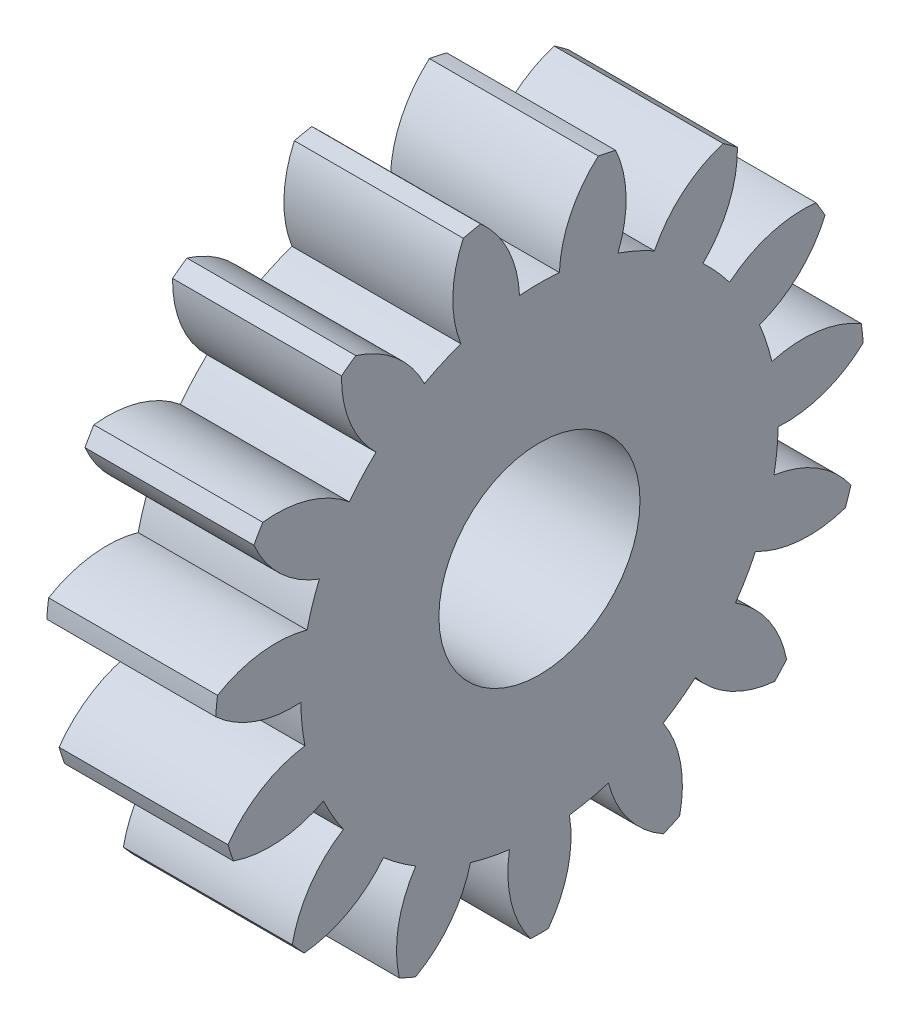
SolidWorks part; units mm, degrees
ref_plane "Plane1" through (0, 0, 0) normal (0, 0, 1) x (1, 0, 0)
ref_plane "Plane2" through (0, 0, 0) normal (0, 1, 0) x (1, 0, 0)
ref_plane "Plane3" through (0, 0, 0) normal (1, 0, 0) x (0, 0, -1)
sketch "HoldingSke" plane through (0, 0, 0) normal (0, 1, 0) x (1, 0, 0)
  line L0 (0, 0) -> (0.5084, -0.1362)
  line L1 (-15, 0) -> (100, 0) construction
  line L2 (0, 0) -> (-2.1039, 2.3779)
  line L3 (0, 0) -> (-11.863, 4.5341)
  line L4 (0, 0) -> (8.3417, 2.2352)
  line L5 (0, 0) -> (-46.8476, -17.4728)
  line L6 (0, 0) -> (-6.9633, -4.6982)
  line L7 (-2.1039, 2.3779) -> (8.6586, 51.2059)
  line L8 (-76.2, 54.61) -> (-74.4, 54.61)
  line L9 (-71.009, 38.7566) -> (-53.1078, 45.2721)
  line L10 (-76.2, 71.12) -> (104.1128, 71.12)
  line L11 (0, 0) -> (-8.4, 0)
  line L12 (-76.2, 101.6) -> (-76.14, 101.6)
  line L13 (24.9733, 27.94) -> (52.9518, 28.4284)
  line L14 (24.9733, 27.94) -> (24.9743, 27.94)
  line L15 (24.9733, 27.94) -> (100.4006, 29.5858)
  line L16 (-63.627, -1.9) -> (-12.827, -1.9)
  circle A0 centre (0, 0) radius 5
  circle A1 centre (0, 0) radius 11.874
  circle A2 centre (0, 0) radius 37.5
  circle A3 centre (0, 0) radius 5
  dimension "MHD" = 23.748
  dimension "Hub_dia" = 75
  dimension "Bore" = 10
  dimension "MBD" = 10
  dimension "Num_teeth" = 15
  dimension "Pitch" = 0.5263
  dimension "Overall_len" = 50
  dimension "Show_teeth" = 15
  dimension "Thickness" = 8.4
  dimension "OAL" = 50.0001
  dimension "T_dim" = 1.8
  dimension "Ap" = 20
  dimension "H" = 19.05
  dimension "Pitch_radius" = 180.3128
  dimension "Width" = 8.4
  dimension "Backlash" = 0.06
  dimension "Addendum_fac" = 1
  dimension "Dedendum_fac" = 1.25
  dimension "Clearance_fac" = 0.25
  dimension "Dedendum_add" = 0.001
  dimension "Module" = 1.9
sketch "BasProSke" plane through (0, 0, 0) normal (0, 1, 0) x (1, 0, 0)
  line L0 (-10, 0) -> (60, 0) construction
  line L1 (0, 0) -> (0, 16.15)
  line L2 (0, 0) -> (8.4, 0)
  line L3 (8.4, 0) -> (8.4, 16.15)
  line L4 (8.4, 16.15) -> (0, 16.15)
  dimension "Thickness" = 8.4
  dimension "Diameter" = 32.3
revolve "Base-Revolve" add sketch "BasProSke" angle 360 about L0
sketch "TooCutSke" plane through (0, 0, 0) normal (1, 0, 0) x (0, 0, -1)
  line L1 (0, 0) -> (0, 107) construction
  line L2 (0, 0) -> (-1.5944, 14.1605) construction
  line L3 (0, 0) -> (-5.8974, 27.7453) construction
  line L4 (-1.5944, 14.1605) -> (-2.9487, 13.8727) construction
  arc A0 (0.9922, 11.8325) -> (-0.9922, 11.8325) centre (0, 0) ccw
  arc A1 (2.9495, 15.9042) -> (-2.9495, 15.9042) centre (0, 0) ccw
  circle A2 centre (0, 0) radius 14.25 construction
  circle A3 centre (0, 0) radius 13.3906 construction
  arc A4 (-0.9922, 11.8325) -> (-2.9495, 15.9042) centre (-6.6875, 11.6011) ccw
  arc A5 (2.9495, 15.9042) -> (0.9922, 11.8325) centre (6.6875, 11.6011) ccw
  dimension "Root_dia" = 23.748
  dimension "Overcut_dia" = 32.3508
  dimension "Pitch_dia" = 28.5
  dimension "Base_dia" = 26.7812
  dimension "Flank_rad" = 5.7
  dimension "Half_ang" = 12
  dimension "Half_CT" = 1.3845
extrude "ToothCut" cut sketch "TooCutSke" along normal through all
fillet "Breaks" [suppressed] radius 0.038
fillet "RootFillets" [suppressed] radius 0.476
pattern_circular "TeethCuts" count 15 every 24 about axis through (-10, 0, 0) along (1, 0, 0) of "ToothCut", "RootFillets", "Breaks"
sketch "HubNeaOneSke" plane through (0, 0, 0) normal (-1, 0, 0) x (0, 0, 1)
  circle A0 centre (0, 0) radius 11.874
  dimension "Diameter" = 23.748
extrude "HubNearOne" [suppressed] add sketch "HubNeaOneSke" along normal blind 41.6001
sketch "HubNeaBotSke" plane through (0, 0, 0) normal (-1, 0, 0) x (0, 0, 1)
  circle A0 centre (0, 0) radius 11.874
  dimension "Diameter" = 23.748
extrude "HubNearBoth" [suppressed] add sketch "HubNeaBotSke" along normal blind 20.8
ref_plane "FarPln" through (8.4, 0, 0) normal (1, 0, 0) x (0, 0, -1)
sketch "HubFarSke" plane through (8.4, 0, 0) normal (1, 0, 0) x (0, 0, -1)
  circle A0 centre (0, 0) radius 11.874
  dimension "Diameter" = 23.748
extrude "HubFar" [suppressed] add sketch "HubFarSke" along normal blind 20.8
sketch "BorSke" plane through (0, 0, 0) normal (1, 0, 0) x (0, 0, -1)
  circle A0 centre (0, 0) radius 5
  dimension "Diameter" = 10
extrude "Bore" cut sketch "BorSke" along normal mid plane 100.0001
sketch "KeySke" plane through (0, 0, 0) normal (1, 0, 0) x (0, 0, -1)
  line L0 (-2, 0) -> (-2, 6.8)
  line L1 (-2, 6.8) -> (2, 6.8)
  line L2 (2, 6.8) -> (2, 0)
  line L3 (0, 0) -> (0, 34) construction
  line L4 (-2, 0) -> (2, 0)
  dimension "Offset" = 6.8
  dimension "Width" = 4
extrude "Keyway" [suppressed] cut sketch "KeySke" along normal mid plane 100.0001
pattern_circular "Keyway2" [suppressed] count 2 every 90 about axis through (-10, 0, 0) along (1, 0, 0)
equation "' \"Module@HoldingSke\" = 6.35"
equation "' \"Num_teeth@HoldingSke\" = 12"
equation "' \"Ap@HoldingSke\" =  20"
equation "' \"Ap@HoldingSke\" = 20"
equation "' \"Width@HoldingSke\" = 0.5 * 25.4"
equation "' \"Hub_dia@HoldingSke\"= 1 * 25.4"
equation "' \"Hub_dia@HoldingSke\" = 1 * 25.4"
equation "' \"Overall_len@HoldingSke\" = 1.0 * 25.4"
equation "' \"Bore@HoldingSke\" = 0.75 * 25.4"
equation "' \"T_dim@HoldingSke\" = 0.1 * 25.4"
equation "' \"Width@KeySke\" = 0.25 * 25.4"
equation "' \"Show_teeth@HoldingSke\" = 13"
equation "' \"Backlash@HoldingSke\" = 0.009 * 25.4"
equation "' \"Addendum_fac@HoldingSke\" = 1.0"
equation "' \"Dedendum_fac@HoldingSke\" = 1.25"
equation "' \"Dedendum_add@HoldingSke\" = 0.00005 * 25.4"
equation "' \"Clearance_fac@HoldingSke\" = 0.25"
equation "\"Pitch@HoldingSke\" = 1 / \"Module@HoldingSke\""
equation "\"Overcut_dia@TooCutSke\" = (\"Num_teeth@HoldingSke\" + 2 * \"Addendum_fac@HoldingSke\") / \"Pitch@HoldingSke\" + 0.002 * 25.4"
equation "\"Pitch_dia@TooCutSke\" = \"Num_teeth@HoldingSke\" / \"Pitch@HoldingSke\""
equation "\"Base_dia@TooCutSke\" = \"Num_teeth@HoldingSke\" / \"Pitch@HoldingSke\" * cos((\"Ap@HoldingSke\"  * 3.14159265 / 180))"
equation "\"Root_dia@TooCutSke\" = (\"Num_teeth@HoldingSke\" + 2) / \"Pitch@HoldingSke\" - 2 * (\"Addendum_fac@HoldingSke\" + \"Dedendum_fac@HoldingSke\") / \"Pitch@HoldingSke\" - \"Dedendum_add@HoldingSke\" * 2"
equation "\"Half_ang@TooCutSke\" = 180 / \"Num_teeth@HoldingSke\""
equation "\"Half_CT@TooCutSke\" = \"Num_teeth@HoldingSke\" / \"Pitch@HoldingSke\" * sin((3.14159265 / 2 / \"Num_teeth@HoldingSke\")) / 2 - 7 * \"Backlash@HoldingSke\" / 4"
equation "\"Flank_rad@TooCutSke\" = \"Num_teeth@HoldingSke\" / \"Pitch@HoldingSke\" / 5"
equation "\"Radius@RootFillets\" = \"Clearance_fac@HoldingSke\" / \"Pitch@HoldingSke\" + \"Dedendum_add@HoldingSke\""
equation "\"Break_rad@Breaks\" = 0.02 / \"Pitch@HoldingSke\""
equation "\"Thickness@HoldingSke\" = \"Width@HoldingSke\""
equation "\"OAL@HoldingSke\" = \"Thickness@HoldingSke\""
equation "\"MHD@HoldingSke\" = (\"Num_teeth@HoldingSke\" + 2) / \"Pitch@HoldingSke\" - 2 * (\"Addendum_fac@HoldingSke\" + \"Dedendum_fac@HoldingSke\")  / \"Pitch@HoldingSke\" - \"Dedendum_add@HoldingSke\" * 2"
equation "\"MBD@HoldingSke\" = (\"Num_teeth@HoldingSke\" + 2) / \"Pitch@HoldingSke\" - 2 * (\"Addendum_fac@HoldingSke\" + \"Dedendum_fac@HoldingSke\")  / \"Pitch@HoldingSke\" - \"Dedendum_add@HoldingSke\" * 2 - 0.002 * 25.4"
equation "\"MHD@HoldingSke\" = ((sgn( \"MHD@HoldingSke\" - \"Hub_dia@HoldingSke\" )-1)*( \"MHD@HoldingSke\" - \"Hub_dia@HoldingSke\" ))/-2+ \"Hub_dia@HoldingSke\""
equation "\"MBD@HoldingSke\" = ((sgn( \"MBD@HoldingSke\" - \"Bore@HoldingSke\" )-1)*( \"MBD@HoldingSke\" - \"Bore@HoldingSke\" ))/-2+ \"Bore@HoldingSke\""
equation "\"OAL@HoldingSke\" = ((sgn( \"OAL@HoldingSke\" - \"Overall_len@HoldingSke\" )+1)*( \"OAL@HoldingSke\" - \"Overall_len@HoldingSke\" ))/2 + \"Overall_len@HoldingSke\" + 0.000002 * 25.4"
equation "\"Num_teeth@TeethCuts\" = int( \"Show_teeth@HoldingSke\" ) + 1"
equation "\"Num_teeth@TeethCuts\" = ((sgn( \"Num_teeth@TeethCuts\" - \"Num_teeth@HoldingSke\" )-1)*( \"Num_teeth@TeethCuts\" - \"Num_teeth@HoldingSke\" ))/-2+ \"Num_teeth@HoldingSke\""
equation "\"Num_teeth@TeethCuts\" = ((sgn( \"Num_teeth@TeethCuts\" - 2.0)+1)*( \"Num_teeth@TeethCuts\" - 2.0))/2 +2.0"
equation "\"Angle@TeethCuts\" = 360.0 / \"Num_teeth@HoldingSke\""
equation "\"Diameter@BasProSke\" = (\"Num_teeth@HoldingSke\" + 2 * \"Addendum_fac@HoldingSke\") / \"Pitch@HoldingSke\""
equation "\"Thickness@BasProSke\"  = \"Thickness@HoldingSke\""
equation "' \"Fillet_rad@BasProSke\" =  \"Thickness@HoldingSke\" * 0.05"
equation "' \"Fillet_rad@BasProSke\" = \"Thickness@HoldingSke\" * 0.05"
equation "\"MHD@HoldingSke\" = ((sgn( \"MHD@HoldingSke\" - \"Root_dia@TooCutSke\" )-1)*( \"MHD@HoldingSke\" - \"Root_dia@TooCutSke\" ))/-2+ \"Root_dia@TooCutSke\""
equation "\"Diameter@HubNeaOneSke\" = \"MHD@HoldingSke\""
equation "\"Length@HubNearOne\" = \"OAL@HoldingSke\" - \"Thickness@BasProSke\""
equation "\"Diameter@HubNeaBotSke\" = \"MHD@HoldingSke\""
equation "\"Length@HubNearBoth\" = ( \"OAL@HoldingSke\" - \"Thickness@BasProSke\" ) / 2.0"
equation "\"Thickness@FarPln\" = \"Thickness@BasProSke\""
equation "\"Diameter@HubFarSke\" = \"MHD@HoldingSke\""
equation "\"Length@HubFar\" = ( \"OAL@HoldingSke\" - \"Thickness@BasProSke\" ) / 2.0"
equation "\"Diameter@BorSke\" = \"MBD@HoldingSke\""
equation "\"D1@Bore\" = \"OAL@HoldingSke\" * 2.0"
equation "\"D1@Keyway\" = \"OAL@HoldingSke\" * 2.0"
equation "\"Offset@KeySke\" = \"T_dim@HoldingSke\" + \"MBD@HoldingSke\" / 2.0"
